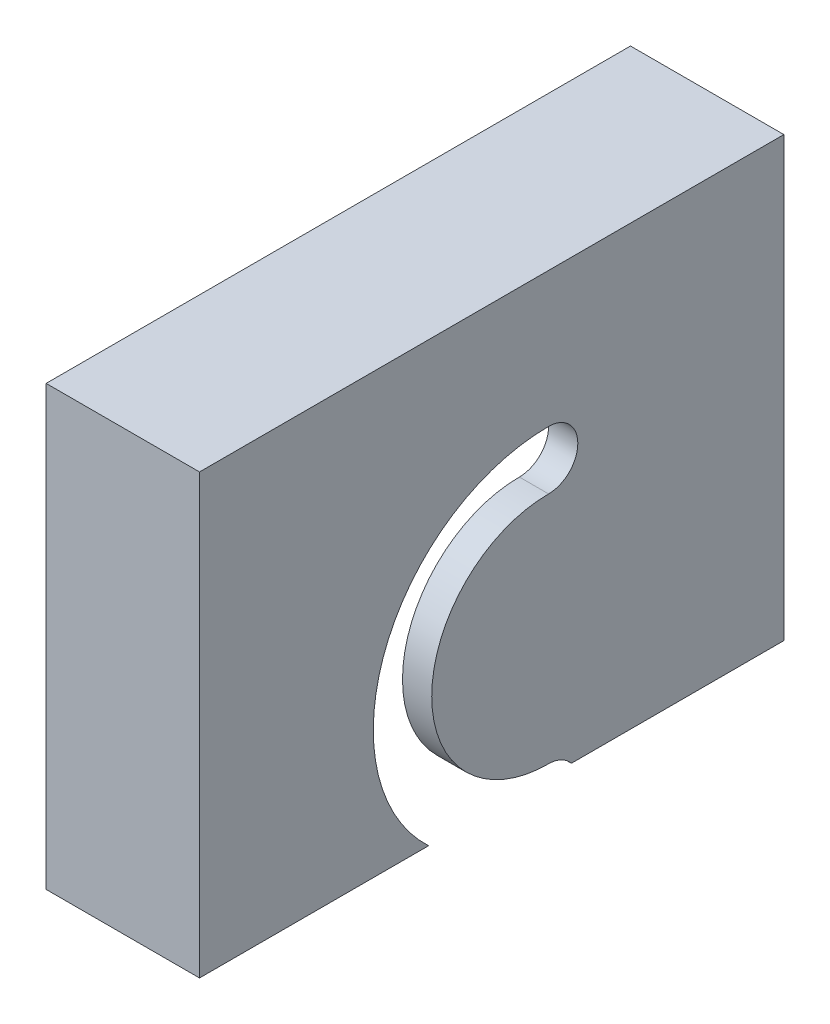
SolidWorks part; units mm, degrees
ref_plane "Front Plane" through (0, 0, 0) normal (0, 0, 1) x (1, 0, 0)
ref_plane "Top Plane" through (0, 0, 0) normal (0, 1, 0) x (1, 0, 0)
ref_plane "Right Plane" through (0, 0, 0) normal (1, 0, 0) x (0, 0, -1)
sketch "Sketch1" plane through (0, 0, 0) normal (1, 0, 0) x (0, 0, -1)
  line L0 (7.79, 30) -> (7.79, -30) construction
  line L1 (-40, 30) -> (40, 30)
  line L2 (-40, 30) -> (-40, -30)
  line L3 (-40, -30) -> (40, -30)
  line L4 (40, 30) -> (40, -30)
  line L5 (40, -12.5) -> (-40, -12.5) construction
  point P4 (0, 30)
  point P6 (40, 0)
  dimension "D1" = 80
  dimension "D2" = 60
  dimension "D3" = 17.5
  dimension "D4" = 32.21
extrude "Boss-Extrude1" add sketch "Sketch1" along normal blind 21
sketch "Sketch2" plane through (21, 0, 0) normal (1, 0, 0) x (0, 0, -1)
  line L0 (40, -30) -> (40, 30) construction
  line L1 (-40, -30) -> (40, -30) construction
  arc A0 (7.79, 11.5) -> (7.79, -36.5) centre (7.79, -12.5) ccw
  arc A1 (7.79, 3.5) -> (7.79, -28.5) centre (7.79, -12.5) ccw
  arc A2 (7.79, 3.5) -> (7.79, 11.5) centre (7.79, 7.5) ccw
  arc A3 (7.79, -36.5) -> (7.79, -28.5) centre (7.79, -32.5) ccw
  point P2 (0, 0)
  point P8 (0, 0)
  point P10 (8.1725, 11.4978)
  point P14 (0, 0)
  point P15 (0, 0)
  point P16 (0, 0)
  point P17 (0, 0)
  dimension "D1" = 8
  dimension "D2" = 32.21
  dimension "D3" = 17.5
  dimension "D4" = 20
extrude "Cut-Extrude1" cut sketch "Sketch2" against normal up to surface (21 mm away) up to face at (0, 0, 0)
sketch "Sketch3" plane through (0, 0, 0) normal (-1, 0, 0) x (0, 0, 1)
  line L0 (-10.9125, -30) -> (-40, -30) construction
  line L1 (-35, -30) -> (35, -30)
  line L2 (-35, -30) -> (-35, 25)
  line L3 (-35, 25) -> (35, 25)
  line L4 (35, -30) -> (35, 25)
  line L5 (-40, 30) -> (40, 30) construction
  line L6 (-40, -30) -> (-40, 30) construction
  line L7 (40, 30) -> (40, -30) construction
  dimension "D1" = 5
  dimension "D2" = 5
  dimension "D3" = 5
extrude "Cut-Extrude2" cut sketch "Sketch3" against normal offset from surface (17 mm away) 4 up to face at (21, -7.507, 0.0316)
